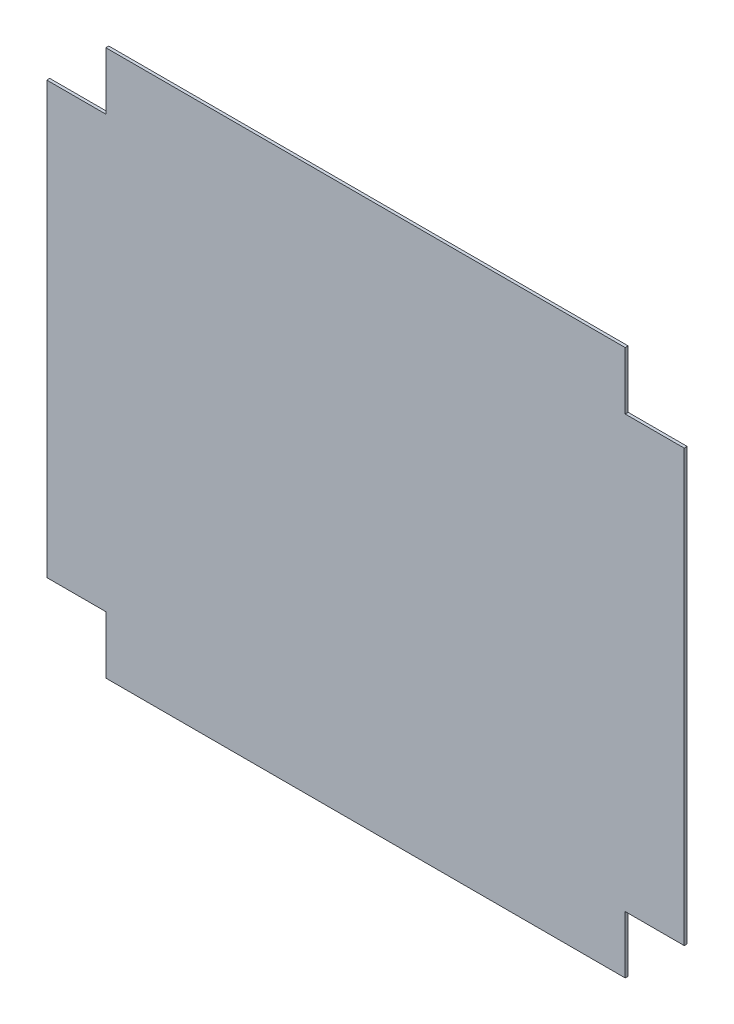
SolidWorks part; units mm, degrees
ref_plane "Alzado" through (0, 0, 0) normal (0, 0, 1) x (1, 0, 0)
ref_plane "Planta" through (0, 0, 0) normal (0, 1, 0) x (1, 0, 0)
ref_plane "Vista lateral" through (0, 0, 0) normal (1, 0, 0) x (0, 0, -1)
sketch "Croquis1" plane through (0, 0, 0) normal (0, 0, 1) x (1, 0, 0)
  line L1 (216, -185) -> (-216, -185)
  line L2 (216, -185) -> (216, 185)
  line L3 (216, 185) -> (-216, 185)
  line L4 (-216, -185) -> (-216, 185)
  line L5 (216, -185) -> (-216, 185) construction
  line L6 (216, 185) -> (-216, -185) construction
  point P0 (0, 0)
  dimension "D1" = 432
  dimension "D2" = 370
extrude "Saliente-Extruir1" add sketch "Croquis1" along normal blind 2
sketch "Croquis2" plane through (0, 0, 2) normal (0, 0, 1) x (1, 0, 0)
  line L0 (-216, 146) -> (-216, -146) construction
  line L5 (176, -185) -> (-176, -185) construction
  line L6 (216, -146) -> (216, 146) construction
  line L12 (-176, 185) -> (176, 185) construction
  line L13 (-216, 185) -> (-176, 185)
  line L14 (-216, 185) -> (-216, 146)
  line L15 (-216, 146) -> (-176, 146)
  line L16 (-176, 185) -> (-176, 146)
  line L17 (216, 185) -> (176, 185)
  line L18 (216, 185) -> (216, 146)
  line L19 (216, 146) -> (176, 146)
  line L20 (176, 185) -> (176, 146)
  line L21 (216, -185) -> (176, -185)
  line L22 (216, -185) -> (216, -146)
  line L23 (216, -146) -> (176, -146)
  line L24 (176, -185) -> (176, -146)
  line L25 (-216, -185) -> (-176, -185)
  line L26 (-216, -185) -> (-216, -146)
  line L27 (-216, -146) -> (-176, -146)
  line L28 (-176, -185) -> (-176, -146)
  point P16 (216, 0)
  point P17 (-216, 0)
  point P18 (0, -185)
  point P19 (0, 185)
  point P20 (0, 0)
  dimension "D1" = 352
  dimension "D2" = 292
extrude "Cortar-Extruir1" cut sketch "Croquis2" against normal through all
